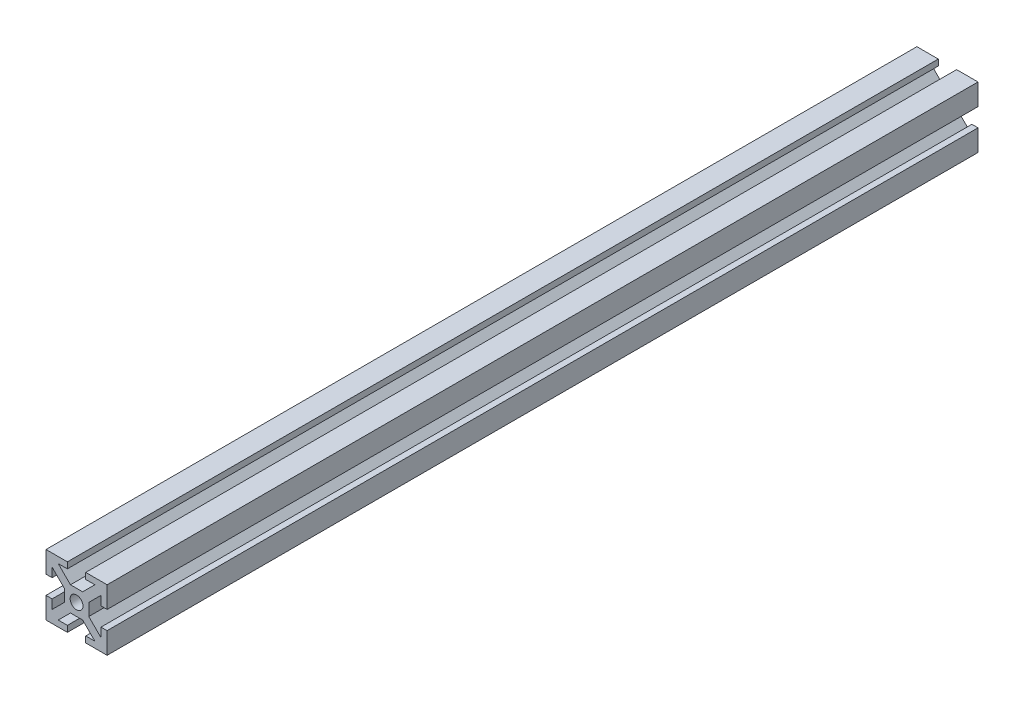
SolidWorks part; units mm, degrees
ref_plane "Front Plane" through (0, 0, 0) normal (0, 0, 1) x (1, 0, 0)
ref_plane "Top Plane" through (0, 0, 0) normal (0, 1, 0) x (1, 0, 0)
ref_plane "Right Plane" through (0, 0, 0) normal (1, 0, 0) x (0, 0, -1)
sketch "Sketch1" plane through (0, 0, 0) normal (0, 0, 1) x (1, 0, 0)
  line L0 (2, 4) -> (2, 7)
  line L9 (0, 0) -> (7, 0)
  line L10 (0, 0) -> (0, 7)
  line L14 (6, 14) -> (6, 6)
  line L15 (6, 6) -> (14, 6)
  line L19 (4, 2) -> (7, 2)
  line L20 (0, 10) -> (20, 10) construction
  line L21 (10, 20) -> (10, 0) construction
  line L22 (0, 7) -> (2, 7)
  line L23 (6, 8) -> (2, 4)
  line L24 (8, 6) -> (4, 2)
  line L25 (0, 0) -> (0, 20) construction
  line L26 (7, 2) -> (7, 0)
  line L27 (2, 2) -> (2, 18) construction
  line L28 (6, 14) -> (14, 14)
  line L29 (2, 2) -> (18, 2) construction
  line L30 (0, 0) -> (20, 0) construction
  line L31 (18, 2) -> (18, 18) construction
  line L32 (20, 0) -> (20, 20) construction
  line L33 (2, 18) -> (18, 18) construction
  line L34 (0, 20) -> (20, 20) construction
  line L35 (7, 18) -> (7, 20)
  line L36 (8, 14) -> (4, 18)
  line L37 (6, 12) -> (2, 16)
  line L38 (0, 13) -> (2, 13)
  line L39 (4, 18) -> (7, 18)
  line L40 (0, 20) -> (0, 13)
  line L41 (0, 20) -> (7, 20)
  line L42 (2, 16) -> (2, 13)
  line L43 (18, 16) -> (18, 13)
  line L44 (20, 20) -> (13, 20)
  line L45 (20, 20) -> (20, 13)
  line L46 (16, 18) -> (13, 18)
  line L47 (20, 13) -> (18, 13)
  line L48 (14, 12) -> (18, 16)
  line L49 (12, 14) -> (16, 18)
  line L50 (13, 18) -> (13, 20)
  line L51 (13, 2) -> (13, 0)
  line L52 (12, 6) -> (16, 2)
  line L53 (14, 8) -> (18, 4)
  line L54 (20, 7) -> (18, 7)
  line L55 (16, 2) -> (13, 2)
  line L56 (14, 14) -> (14, 6)
  line L57 (20, 0) -> (20, 7)
  line L58 (20, 0) -> (13, 0)
  line L59 (18, 4) -> (18, 7)
  circle A1 centre (10, 10) radius 2.1
  point P24 (0, 7)
  point P25 (2, 7)
  point P28 (10, 6)
  point P31 (6, 10)
  point P42 (10, 14)
  point P60 (14, 10)
  dimension "D5" = 3
  dimension "D3" = 4.2
  dimension "D7" = 2.1
  dimension "D1" = 20
  dimension "D4" = 2
  dimension "D6" = 3
  dimension "D8" = 4
  dimension "D9" = 4
  dimension "D10" = 10
  dimension "D11" = 10
  dimension "D12" = 10
  dimension "D13" = 10
  dimension "D14" = 6
  dimension "D15" = 45
  dimension "D16" = 6
  dimension "D17" = 45
extrude "Boss-Extrude1" add sketch "Sketch1" along normal blind 285 contours L42 L37 L14 L28 L36 L39 L35 L41 L40 L38 | L28 L56 L48 L43 L47 L45 L44 L50 L46 L49 | L56 L28 L14 L15 A1 | L26 L19 L24 L15 L14 L23 L0 L22 L10 L9 | L59 L53 L56 L15 L52 L55 L51 L58 L57 L54
